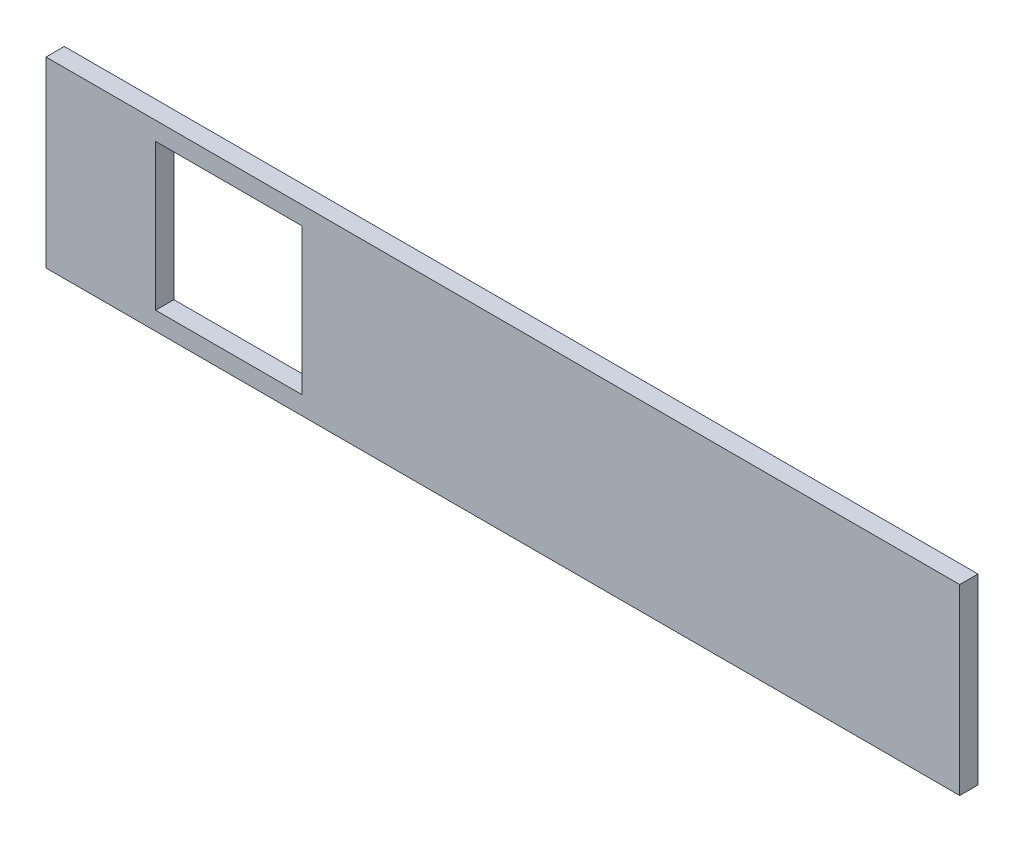
SolidWorks part; units mm, degrees
material "Balsa"
ref_plane "Plan de face" through (0, 0, 0) normal (0, 0, 1) x (1, 0, 0)
ref_plane "Plan de dessus" through (0, 0, 0) normal (0, 1, 0) x (1, 0, 0)
ref_plane "Plan de droite" through (0, 0, 0) normal (1, 0, 0) x (0, 0, -1)
sketch "Esquisse1" plane through (0, 0, 0) normal (0, 0, 1) x (1, 0, 0)
  line L1 (0, 0) -> (-500, 0)
  line L2 (0, 0) -> (0, 100)
  line L3 (0, 100) -> (-500, 100)
  line L4 (-500, 0) -> (-500, 100)
  line L5 (-440, 90) -> (-360, 90)
  line L6 (-440, 90) -> (-440, 10)
  line L7 (-440, 10) -> (-360, 10)
  line L8 (-360, 90) -> (-360, 10)
  point P11 (-864.8875, 7.7859)
  dimension "D1" = 500
  dimension "D2" = 100
  dimension "D3" = 80
  dimension "D4" = 80
  dimension "D5" = 10
  dimension "D6" = 60
extrude "Boss.-Extru.1" add sketch "Esquisse1" along normal blind 10
